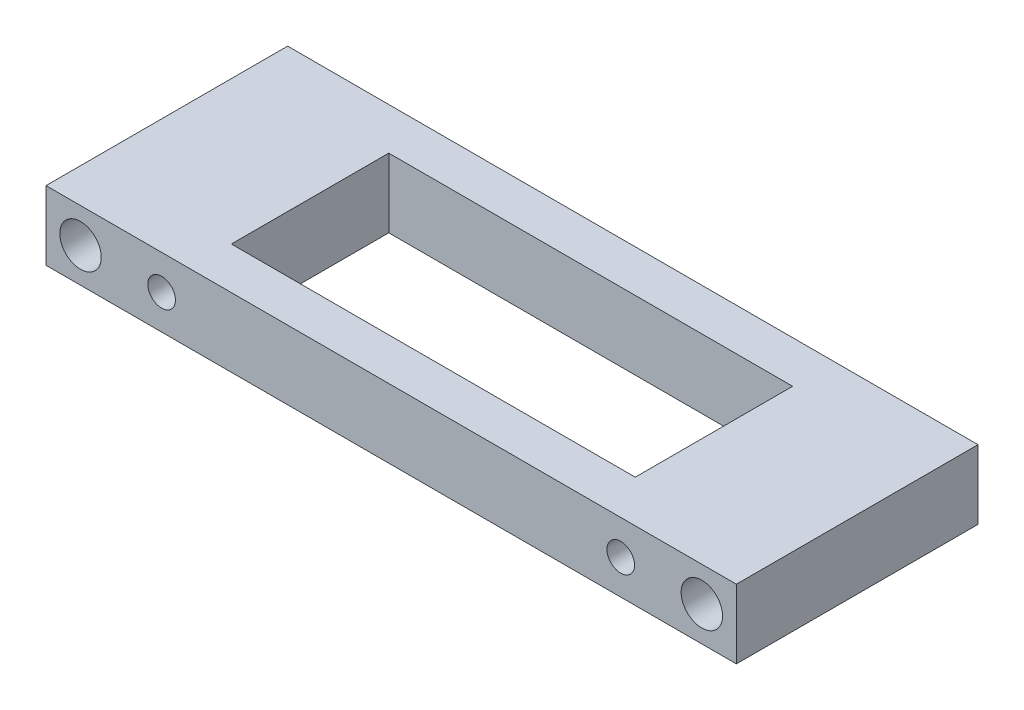
SolidWorks part; units mm, degrees
ref_plane "Front Plane" through (0, 0, 0) normal (0, 0, 1) x (1, 0, 0)
ref_plane "Top Plane" through (0, 0, 0) normal (0, 1, 0) x (1, 0, 0)
ref_plane "Right Plane" through (0, 0, 0) normal (1, 0, 0) x (0, 0, -1)
sketch "Sketch1" plane through (0, 0, 0) normal (0, 0, 1) x (1, 0, 0)
  line L0 (-58.5, 20) -> (-58.5, 0) construction
  line L1 (0, 0) -> (-100, 0)
  line L2 (0, 0) -> (0, 20)
  line L3 (0, 20) -> (-100, 20)
  line L4 (-100, 0) -> (-100, 20)
  circle A0 centre (-90, 10) radius 6
  circle A1 centre (-66.5, 10) radius 4
  point P9 (-100, 10)
  dimension "D3" = 12
  dimension "D4" = 8
  dimension "D1" = 100
  dimension "D2" = 20
  dimension "D5" = 23.5
  dimension "D6" = 10
  dimension "D7" = 8
  dimension "D8" = 41.5
extrude "Boss-Extrude1" add sketch "Sketch1" along normal blind 40
sketch "Sketch2" plane through (0, 0, 0) normal (0, 0, -1) x (-1, 0, 0)
  line L1 (100, 20) -> (0, 20)
  line L2 (100, 20) -> (100, 0)
  line L3 (100, 0) -> (0, 0)
  line L4 (0, 20) -> (0, 0)
extrude "Boss-Extrude2" add sketch "Sketch2" along normal blind 30
sketch "Sketch3" plane through (0, 20, 0) normal (0, 1, 0) x (1, 0, 0)
  line L0 (0, -40) -> (0, 30) construction
  line L1 (0, 17.8) -> (-58.5, 17.8)
  line L2 (0, 17.8) -> (0, -27.8)
  line L3 (0, -27.8) -> (-58.5, -27.8)
  line L4 (-58.5, 17.8) -> (-58.5, -27.8)
  line L5 (-100, -40) -> (-100, 30) construction
  line L6 (-100, 30) -> (0, 30) construction
  line L7 (0, -40) -> (-100, -40) construction
  dimension "D1" = 41.5
  dimension "D2" = 12.2
  dimension "D3" = 12.2
extrude "Cut-Extrude1" cut sketch "Sketch3" against normal up to next
mirror "Mirror2" about plane through (0, 0, 40) normal (-1, 0, 0) of "Boss-Extrude2", "Cut-Extrude1", "Boss-Extrude1"
